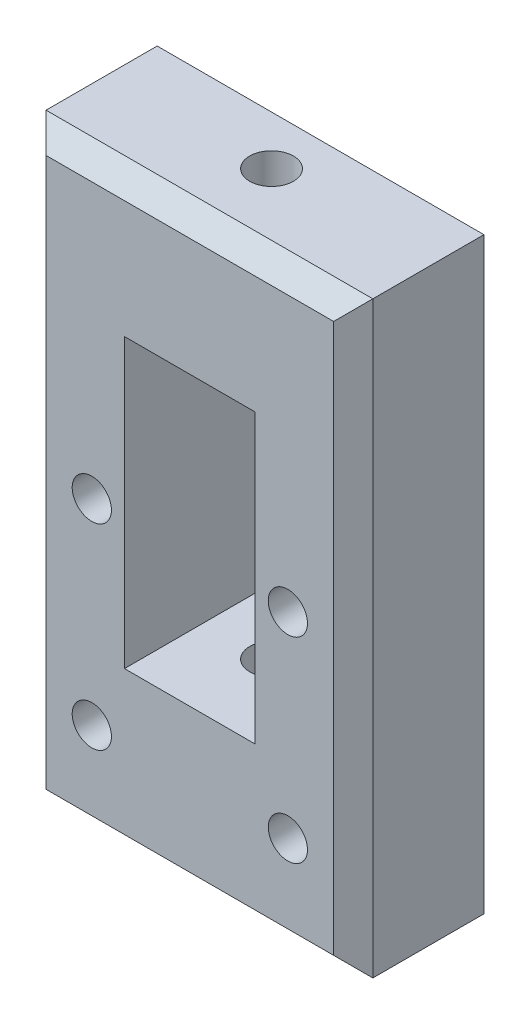
SolidWorks part; units mm, degrees
ref_plane "Front Plane" through (0, 0, 0) normal (0, 0, 1) x (1, 0, 0)
ref_plane "Top Plane" through (0, 0, 0) normal (0, 1, 0) x (1, 0, 0)
ref_plane "Right Plane" through (0, 0, 0) normal (1, 0, 0) x (0, 0, -1)
sketch "Sketch1" plane through (0, 0, 0) normal (0, 0, 1) x (1, 0, 0)
  line L4 (75, 95) -> (125, 95)
  line L5 (75, 95) -> (75, 5)
  line L6 (75, 5) -> (125, 5)
  line L7 (125, 95) -> (125, 5)
  line L8 (75, 95) -> (125, 5) construction
  line L9 (75, 5) -> (125, 95) construction
  circle A0 centre (115, 20) radius 3 construction
  circle A1 centre (85, 20) radius 3 construction
  circle A4 centre (115, 20) radius 3
  circle A5 centre (85, 20) radius 3
  circle A8 centre (85, 50) radius 3
  circle A9 centre (115, 50) radius 3
  point P14 (100, 50)
extrude "Boss-Extrude1" add sketch "Sketch1" along normal blind 20
sketch "Sketch2" plane through (0, 95, 0) normal (0, 1, 0) x (1, 0, 0)
  circle A0 centre (100, -7.5) radius 3.35
extrude "Cut-Extrude1" cut sketch "Sketch2" against normal through all
sketch "Sketch3" plane through (0, 0, 20) normal (0, 0, 1) x (1, 0, 0)
  line L0 (90, 70) -> (90, 74)
  line L2 (110, 70) -> (110, 30)
  line L3 (110, 30) -> (90, 30)
  line L12 (90, 30) -> (90, 70)
  line L14 (90, 74) -> (110, 74)
  line L15 (110, 74) -> (110, 70)
extrude "Cut-Extrude2" cut sketch "Sketch3" against normal through all
chamfer "Chamfer1" distance 3 angle 45 4 edges at (100, 5, 20) (125, 50, 20) (100, 95, 20) (75, 50, 20)
